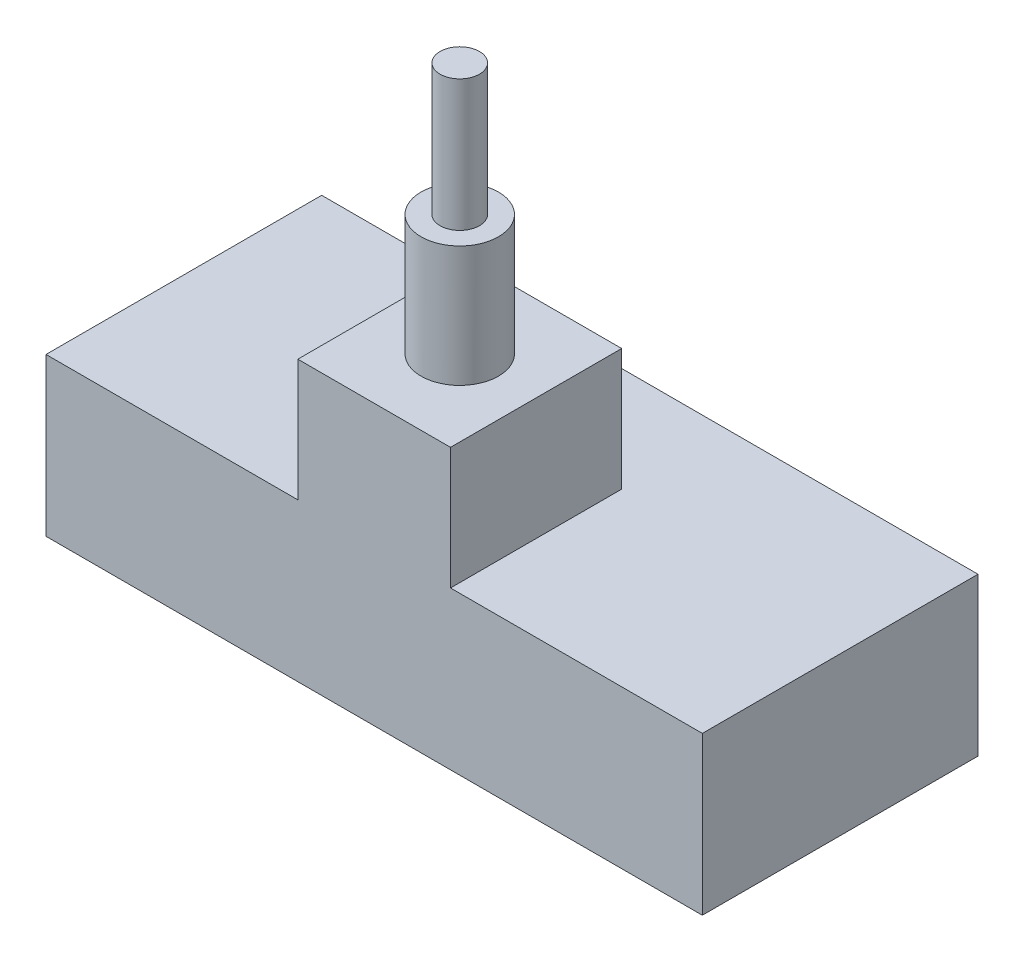
SolidWorks part; units mm, degrees
ref_plane "Front Plane" through (0, 0, 0) normal (0, 0, 1) x (1, 0, 0)
ref_plane "Top Plane" through (0, 0, 0) normal (0, 1, 0) x (1, 0, 0)
ref_plane "Right Plane" through (0, 0, 0) normal (1, 0, 0) x (0, 0, -1)
sketch "Sketch1" plane through (0, 0, 0) normal (0, 1, 0) x (1, 0, 0)
  line L1 (-5.815, -6.52) -> (5.815, -6.52)
  line L2 (-5.815, -6.52) -> (-5.815, 6.52)
  line L3 (-5.815, 6.52) -> (5.815, 6.52)
  line L4 (5.815, -6.52) -> (5.815, 6.52)
  line L5 (-5.815, -6.52) -> (5.815, 6.52) construction
  line L6 (-5.815, 6.52) -> (5.815, -6.52) construction
  point P0 (0, 0)
  dimension "D1" = 11.63
  dimension "D2" = 13.04
extrude "Boss-Extrude1" add sketch "Sketch1" along normal blind 9.28
sketch "Sketch2" plane through (0, 0, 0) normal (0, -1, 0) x (1, 0, 0)
  line L0 (0, 6.52) -> (0, -14.48) construction
  line L1 (-25, 6.52) -> (25, 6.52)
  line L2 (-25, 6.52) -> (-25, -14.48)
  line L3 (-25, -14.48) -> (25, -14.48)
  line L4 (25, 6.52) -> (25, -14.48)
  line L5 (-5.815, 6.52) -> (5.815, 6.52) construction
  dimension "D1" = 50
  dimension "D2" = 21
extrude "Boss-Extrude2" add sketch "Sketch2" along normal blind 12
sketch "Sketch3" plane through (0, 9.28, 0) normal (0, 1, 0) x (1, 0, 0)
  circle A0 centre (0, 0) radius 2.95
  dimension "D1" = 5.9
extrude "Boss-Extrude3" add sketch "Sketch3" along normal blind 9.2
sketch "Sketch4" plane through (0, 18.48, 0) normal (0, 1, 0) x (1, 0, 0)
  circle A0 centre (0, 0) radius 1.5
  dimension "D1" = 3
extrude "Boss-Extrude4" add sketch "Sketch4" along normal blind 10
